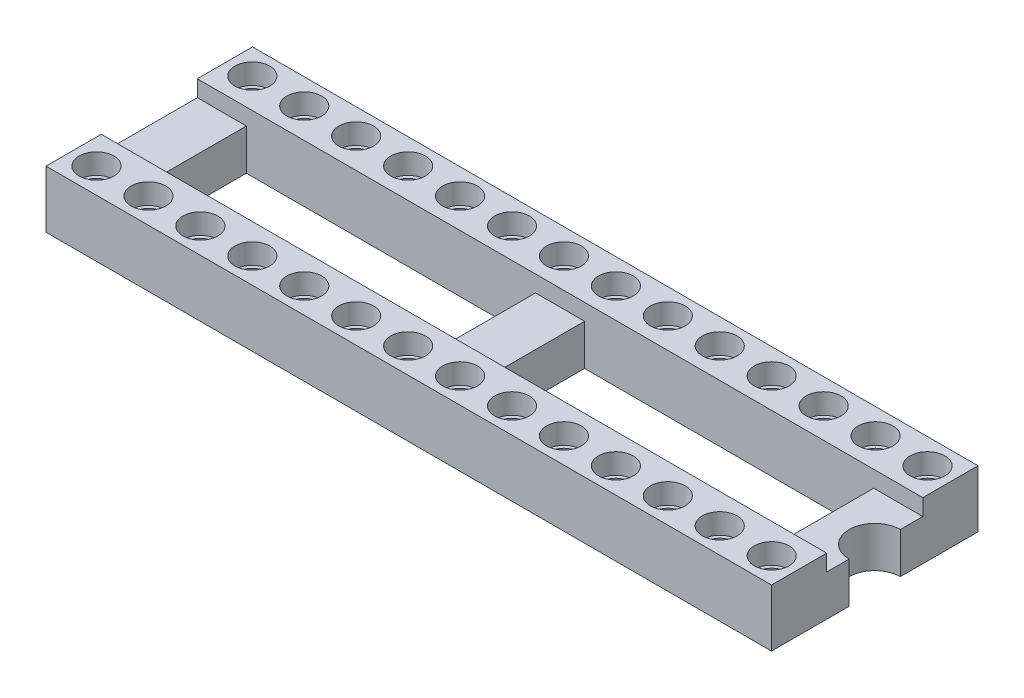
SolidWorks part; units mm, degrees
ref_plane "Front Plane" through (0, 0, 0) normal (0, 0, 1) x (1, 0, 0)
ref_plane "Top Plane" through (0, 0, 0) normal (0, 1, 0) x (1, 0, 0)
ref_plane "Right Plane" through (0, 0, 0) normal (1, 0, 0) x (0, 0, -1)
sketch "Sketch1" plane through (0, 0, 0) normal (1, 0, 0) x (0, 0, -1)
  line L1 (-5.05, 2) -> (5.05, 2)
  line L2 (-5.05, 2) -> (-5.05, 0)
  line L3 (-5.05, 0) -> (5.05, 0)
  line L4 (5.05, 2) -> (5.05, 0)
  line L5 (-5.05, 2) -> (5.05, 0) construction
  line L6 (-5.05, 0) -> (5.05, 2) construction
  line L7 (-5.05, 2.8) -> (-2.35, 2.8)
  line L8 (-5.05, 2.8) -> (-5.05, 0)
  line L9 (-5.05, 0) -> (-2.35, 0)
  line L10 (-2.35, 2.8) -> (-2.35, 0)
  line L11 (-5.05, 2.8) -> (-2.35, 0) construction
  line L12 (-5.05, 0) -> (-2.35, 2.8) construction
  line L13 (2.35, 2.8) -> (5.05, 2.8)
  line L14 (2.35, 2.8) -> (2.35, 0)
  line L15 (2.35, 0) -> (5.05, 0)
  line L16 (5.05, 2.8) -> (5.05, 0)
  line L17 (2.35, 2.8) -> (5.05, 0) construction
  line L18 (2.35, 0) -> (5.05, 2.8) construction
  point P0 (0, 1)
  point P5 (3.7, 1.4)
  point P6 (-3.7, 1.4)
  point P16 (4.0399, 4.6289)
  dimension "D1" = 2
  dimension "D2" = 10.1
  dimension "D3" = 4.7
  dimension "D4" = 2.8
extrude "Boss-Extrude1" add sketch "Sketch1" along normal mid plane 35.48 contours L10 L1 L2 L3 | L10 L7 L8 L1 | L14 L1 L10 L3 | L1 L14 L3 L4 | L16 L13 L14 L1
sketch "Sketch2" plane through (0, 2, 0) normal (0, 1, 0) x (1, 0, 0)
  line L1 (-15.34, 2.35) -> (-1.2, 2.35)
  line L2 (-15.34, 2.35) -> (-15.34, -2.35)
  line L3 (-15.34, -2.35) -> (-1.2, -2.35)
  line L4 (-1.2, 2.35) -> (-1.2, -2.35)
  line L5 (-15.34, 2.35) -> (-1.2, -2.35) construction
  line L6 (-15.34, -2.35) -> (-1.2, 2.35) construction
  line L7 (1.2, 2.35) -> (15.34, 2.35)
  line L8 (1.2, 2.35) -> (1.2, -2.35)
  line L9 (1.2, -2.35) -> (15.34, -2.35)
  line L10 (15.34, 2.35) -> (15.34, -2.35)
  line L11 (1.2, 2.35) -> (15.34, -2.35) construction
  line L12 (1.2, -2.35) -> (15.34, 2.35) construction
  line L14 (17.74, 2.35) -> (-17.74, 2.35) construction
  line L15 (-17.74, -2.35) -> (-17.74, 2.35) construction
  line L16 (17.74, -2.35) -> (17.74, 2.35) construction
  circle A0 centre (17.74, 0) radius 1.25
  point P0 (-8.27, 0)
  point P5 (8.27, 0)
  dimension "D4" = 2.5
  dimension "D1" = 2.4
  dimension "D2" = 2.4
  dimension "D3" = 2.4
extrude "Cut-Extrude1" cut sketch "Sketch2" against normal through all
hole_wizard "CBORE for M5 Hex Head Bolt2" positions "Sketch5" profile "Sketch6" counterbore size "M5" standard "ISO" end condition through all
sketch "Sketch5" plane through (0, 2.8, 0) normal (0, 1, 0) x (1, 0, 0)
  line L0 (0, 0) -> (16.51, 3.81) construction
  point P2 (16.51, 3.81)
  dimension "D1" = 3.81
  dimension "D2" = 16.51
sketch "Sketch6" plane through (16.51, 2.8, -3.81) normal (1, 0, 0) x (0, 0, 1)
  line L0 (0, 0) -> (0, 2.8)
  line L1 (0, 2.8) -> (0.675, 2.8)
  line L3 (0.675, 2.8) -> (0.675, 1)
  line L4 (0.675, 1) -> (0.85, 1)
  line L5 (0.85, 1) -> (0.85, 0)
  line L7 (0.85, 0) -> (0, 0)
  line L11 (0, -6.35) -> (0, 107.95) construction
  dimension "Thru Hole Dia." = 1.35
  dimension "Thru Hole Depth" = 2.8
  dimension "C'Bore Dia." = 1.7
  dimension "C'Bore Depth" = 1
pattern_linear "LPattern1" count 14 spacing 2.54 along (-1, 0, 0) count 2 spacing 7.62 along (0, 0, 1) of "CBORE for M5 Hex Head Bolt2"
